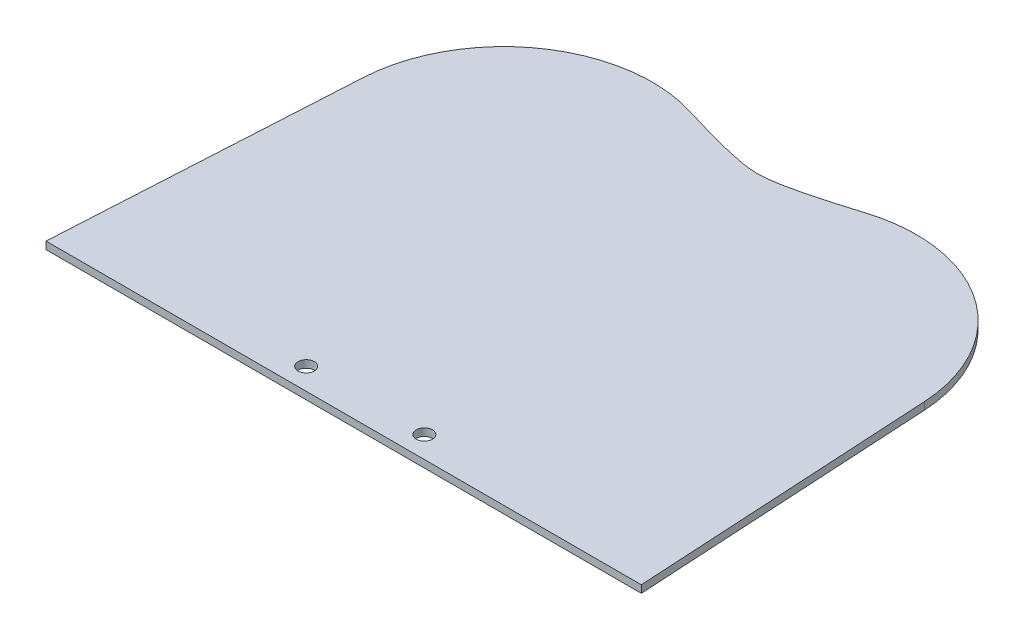
SolidWorks part; units mm, degrees
ref_plane "Front Plane" through (0, 0, 0) normal (0, 0, 1) x (1, 0, 0)
ref_plane "Top Plane" through (0, 0, 0) normal (0, 1, 0) x (1, 0, 0)
ref_plane "Right Plane" through (0, 0, 0) normal (1, 0, 0) x (0, 0, -1)
sketch "Sketch1" plane through (0, 0, 0) normal (0, 1, 0) x (1, 0, 0)
  line L1 (0, 0) -> (160, 0)
  line L2 (0, 0) -> (0, 120)
  line L3 (0, 120) -> (160, 120)
  line L4 (160, 0) -> (160, 120)
  dimension "D1" = 160
  dimension "D2" = 120
extrude "Boss-Extrude1" add sketch "Sketch1" along normal blind 2
sketch "Sketch4" plane through (0, 2, 0) normal (0, 1, 0) x (1, 0, 0)
  line L0 (0, 0) -> (160, 0) construction
  circle A0 centre (95.87, 5.81) radius 2.185
  circle A1 centre (64.12, 5.81) radius 2.185
  dimension "D1" = 4.37
  dimension "D2" = 4.37
  dimension "D3" = 31.75
  dimension "D4" = 5.81
  dimension "D5" = 64.12
  dimension "D6" = 5.81
extrude "Cut-Extrude2" cut sketch "Sketch4" against normal up to surface (2 mm away) up to face at (80, 0, -60)
sketch "Sketch7" plane through (0, 2, 0) normal (0, 1, 0) x (1, 0, 0)
  line L0 (160, 0) -> (155.4151, 80.7542)
  line L1 (80, -6.6662) -> (80, 126.6662) construction
  line L2 (0, 120) -> (0, 0) construction
  line L3 (56.3933, 116.6841) -> (73.7903, 111.2767) construction
  line L4 (103.6067, 116.6841) -> (86.2097, 111.2767) construction
  line L5 (86.2097, 111.2767) -> (80, 111.2767) construction
  line L6 (73.7903, 111.2767) -> (80, 111.2767) construction
  line L7 (0, 0) -> (4.5849, 80.7542)
  line L8 (160, 0) -> (160, 134.8088)
  line L9 (160, 134.8088) -> (0, 134.8088)
  line L10 (0, 134.8088) -> (0, 0)
  arc A0 (155.4151, 80.7542) -> (103.6067, 116.6841) centre (115.4794, 78.4868) ccw
  arc A1 (4.5849, 80.7542) -> (56.3933, 116.6841) centre (44.5206, 78.4868) cw
  spline S0 degree 2 poles (103.6067, 116.6841) (86.2097, 111.2767) (80, 111.2767) knots 0 0 0 1 1 1
  spline S1 degree 2 poles (56.3933, 116.6841) (73.7903, 111.2767) (80, 111.2767) knots 0 0 0 1 1 1
  point P10 (103.1691, 104.4998)
  point P15 (56.8309, 104.4998)
  point P19 (93.7063, 98.8344)
  point P20 (37.6549, 112.3399)
  point P21 (0, 0)
  point P22 (155.4389, 80.7498)
  point P23 (80, 111.0107)
  point P24 (74.646, 111.0107)
  point P25 (86.2097, 111.2767)
  dimension "D2" = 40
  dimension "D1" = 80
extrude "Cut-Extrude4" cut sketch "Sketch7" against normal up to surface (2 mm away) up to face at (64.12, 0, -7.995)
